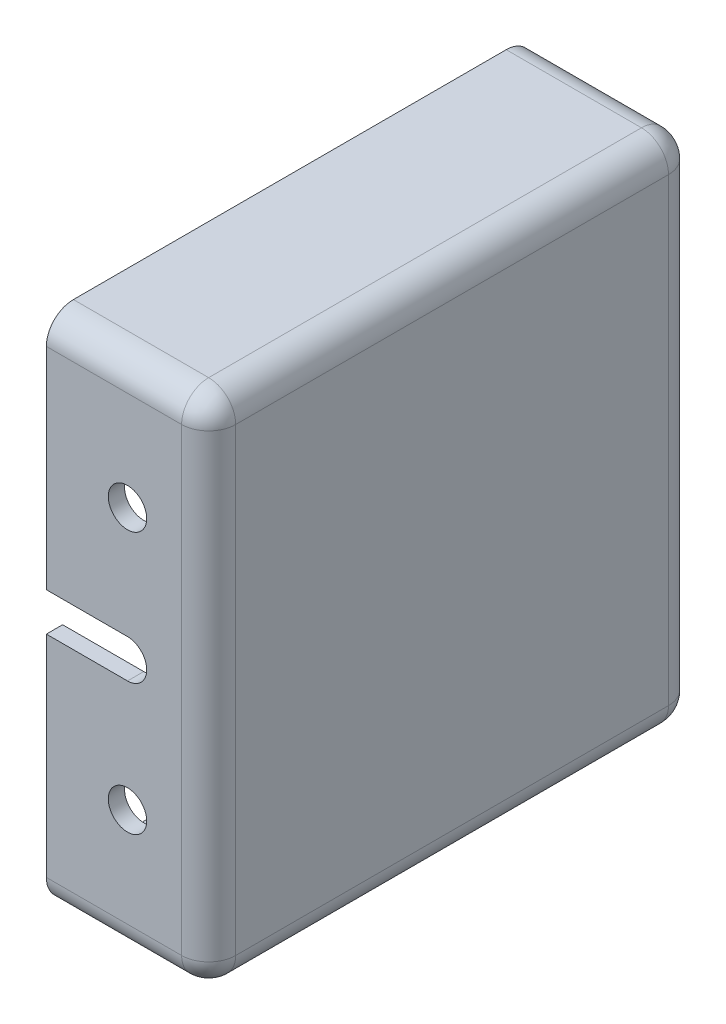
SolidWorks part; units mm, degrees
ref_plane "Front Plane" through (0, 0, 0) normal (1, 0, 0) x (0, 1, 0)
ref_plane "Top Plane" through (0, 0, 0) normal (0, 0, 1) x (0, 1, 0)
ref_plane "Right Plane" through (0, 0, 0) normal (0, 1, 0) x (-1, 0, 0)
sketch "Sketch1" plane through (0, 0, 0) normal (0, 0, 1) x (0, 1, 0)
  line L1 (-47.5, -15) -> (47.5, -15)
  line L2 (-47.5, -15) -> (-47.5, 15)
  line L3 (-47.5, 15) -> (47.5, 15)
  line L4 (47.5, -15) -> (47.5, 15)
  line L5 (-47.5, -15) -> (47.5, 15) construction
  line L6 (-47.5, 15) -> (47.5, -15) construction
  line L7 (0, 15) -> (0, -15) construction
  circle A0 centre (0, 0) radius 3
  point P0 (0, 0)
  dimension "D3" = 6
  dimension "D1" = 30
  dimension "D2" = 95
extrude "Boss-Extrude1" add sketch "Sketch1" along normal blind 90
shell "2 mm top/bot 3 mm side" thickness 3
sketch "Sketch3" plane through (0, 0, 0) normal (0, 0, -1) x (1, 0, 0)
  line L0 (0, 47.5) -> (0, -47.5) construction
  line L1 (15, 47.5) -> (-15, 47.5) construction
  line L2 (15, -47.5) -> (-15, -47.5) construction
  line L4 (0, -47.5) -> (0, -27.5)
  line L5 (0, 47.5) -> (0, 37.5)
  circle A0 centre (0, 32.5) radius 5
  circle A4 centre (0, 12.5) radius 5
  circle A5 centre (0, -7.5) radius 5
  circle A6 centre (0, -27.5) radius 5
  dimension "D1" = 10
  dimension "D3" = 10
  dimension "D2" = 4
sketch "Sketch4" plane through (0, 0, 90) normal (0, 0, 1) x (1, 0, 0)
  line L0 (0, 47.5) -> (0, -47.5) construction
  line L1 (15, 47.5) -> (-15, 47.5) construction
  line L2 (15, -47.5) -> (-15, -47.5) construction
  line L3 (0, 3.55) -> (0, 20.65)
  line L4 (-15, 0) -> (15, 0) construction
  line L5 (-15, -47.5) -> (-15, 47.5) construction
  line L6 (15, -47.5) -> (15, 47.5) construction
  line L7 (0, 3.55) -> (-15, 3.55)
  line L8 (0, -3.55) -> (-15, -3.55)
  line L9 (-15, -3.55) -> (-15, 3.55)
  circle A0 centre (0, 0) radius 3.55
  circle A1 centre (0, 24.2) radius 3.55
  circle A2 centre (0, -24.2) radius 3.55
  line M6 (-15, 47.5) -> (-15, -47.5)
  dimension "D1" = 7.1
  dimension "D2" = 17.1
extrude "7.1 mm fixture holes" cut sketch "Sketch4" along direction (0, 0, 1) on the side against the normal blind 10 contours A1 | A0 | A2 | A0 L7 L8 M6
fillet "5 mm radius" radius 5 16 edges at (12, 42.5, 45) (12, -42.5, 45) (15, -47.5, 45) (15, 47.5, 45) (-1.5, 42.5, 87) (-1.5, -42.5, 87) (15, 0, 90) (15, 0, 0) (12, 0, 3) (-1.5, -42.5, 3) (-1.5, 42.5, 3) (12, 0, 87) (0, 47.5, 90) (0, 47.5, 0) (0, -47.5, 0) (0, -47.5, 90)
extrude "Cut-Extrude1" cut sketch "Sketch3" against normal blind 10 contours A0 L0 | L0 A0 | A4 L0 | L0 A4 | A5 L0 | L0 A5 | L0 A6 L4 | A6 L0 L4
